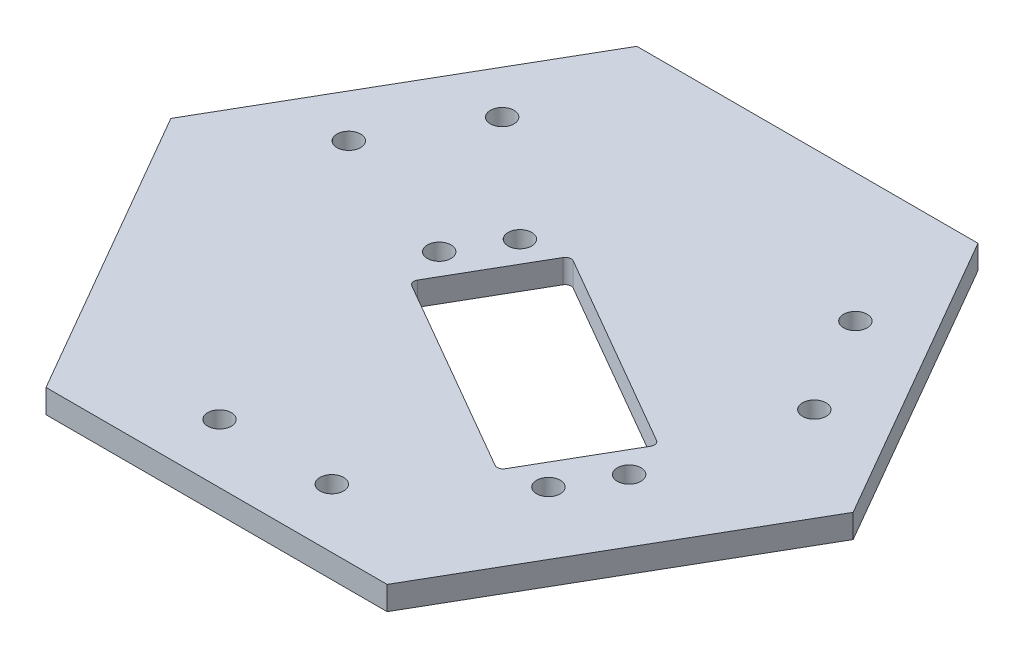
SolidWorks part; units mm, degrees
ref_plane "Front Plane" through (0, 0, 0) normal (0, 0, 1) x (1, 0, 0)
ref_plane "Top Plane" through (0, 0, 0) normal (0, 1, 0) x (1, 0, 0)
ref_plane "Right Plane" through (0, 0, 0) normal (1, 0, 0) x (0, 0, -1)
sketch "Sketch1" plane through (0, 0, 0) normal (0, 1, 0) x (1, 0, 0)
  line L0 (0, 0) -> (43.3013, 25) construction
  line L1 (-28.8675, 50) -> (-57.735, 0)
  line L2 (-28.8675, -50) -> (28.8675, -50)
  line L3 (57.735, 0) -> (28.8675, 50)
  line L4 (0, 0) -> (-43.3013, 25) construction
  line L5 (0, 0) -> (0, -50) construction
  line L6 (29.891, 28.2272) -> (39.391, 11.7728) construction
  line L7 (-9.5, -40) -> (9.5, -40) construction
  line L8 (-57.735, 0) -> (-28.8675, -50)
  line L9 (28.8675, -50) -> (57.735, 0)
  line L10 (-28.8675, 50) -> (28.8675, 50)
  circle A0 centre (0, 0) radius 50 construction
  circle A1 centre (29.891, 28.2272) radius 2
  circle A2 centre (39.391, 11.7728) radius 2
  circle A3 centre (-9.5, -40) radius 2
  circle A4 centre (9.5, -40) radius 2
  circle A5 centre (-39.391, 11.7728) radius 2
  circle A6 centre (-29.891, 28.2272) radius 2
  dimension "D1" = 100
  dimension "D5" = 4
  dimension "D6" = 4
  dimension "D7" = 9.5
  dimension "D8" = 9.5
  dimension "D2" = 9.5
  dimension "D3" = 9.5
  dimension "D4" = 10
  dimension "D9" = 10
  dimension "D10" = 25
  dimension "D11" = 25
  dimension "D12" = 25
  dimension "D13" = 28.8675
extrude "Boss-Extrude1" add sketch "Sketch1" along normal mid plane 4
sketch "Sketch2" plane through (0, 2, 0) normal (0, 1, 0) x (1, 0, 0)
  point P0 (0, 0)
sketch "Sketch3" plane through (0, 2, 0) normal (0, 1, 0) x (1, 0, 0)
  line L0 (0, 0) -> (-8.6603, 5) construction
  line L1 (-13.6603, -3.6603) -> (-3.6603, 13.6603)
  line L2 (-13.6603, -3.6603) -> (21.4138, -23.9103)
  line L3 (21.4138, -23.9103) -> (31.4138, -6.5897)
  line L4 (-3.6603, 13.6603) -> (31.4138, -6.5897)
  line L5 (0, 0) -> (84.6943, 0) construction
  line L6 (-10.4904, 11.8301) -> (33.2439, -13.4199) construction
  circle A0 centre (-10.4904, 11.8301) radius 2
  circle A1 centre (33.2439, -13.4199) radius 2
  circle A2 centre (28.2439, -22.0801) radius 2
  circle A3 centre (-15.4904, 3.1699) radius 2
  dimension "D5" = 4
  dimension "D1" = 20
  dimension "D2" = 40.5
  dimension "D3" = 150
  dimension "D4" = 10
  dimension "D6" = 5
  dimension "D7" = 5
  dimension "D8" = 5
extrude "Cut-Extrude1" cut sketch "Sketch3" against normal blind 10
fillet "Fillet1" radius 1 4 edges at (21.4138, 0, 23.9103) (-13.6603, 0, 3.6603) (31.4138, 0, 6.5897) (-3.6603, 0, -13.6603)
